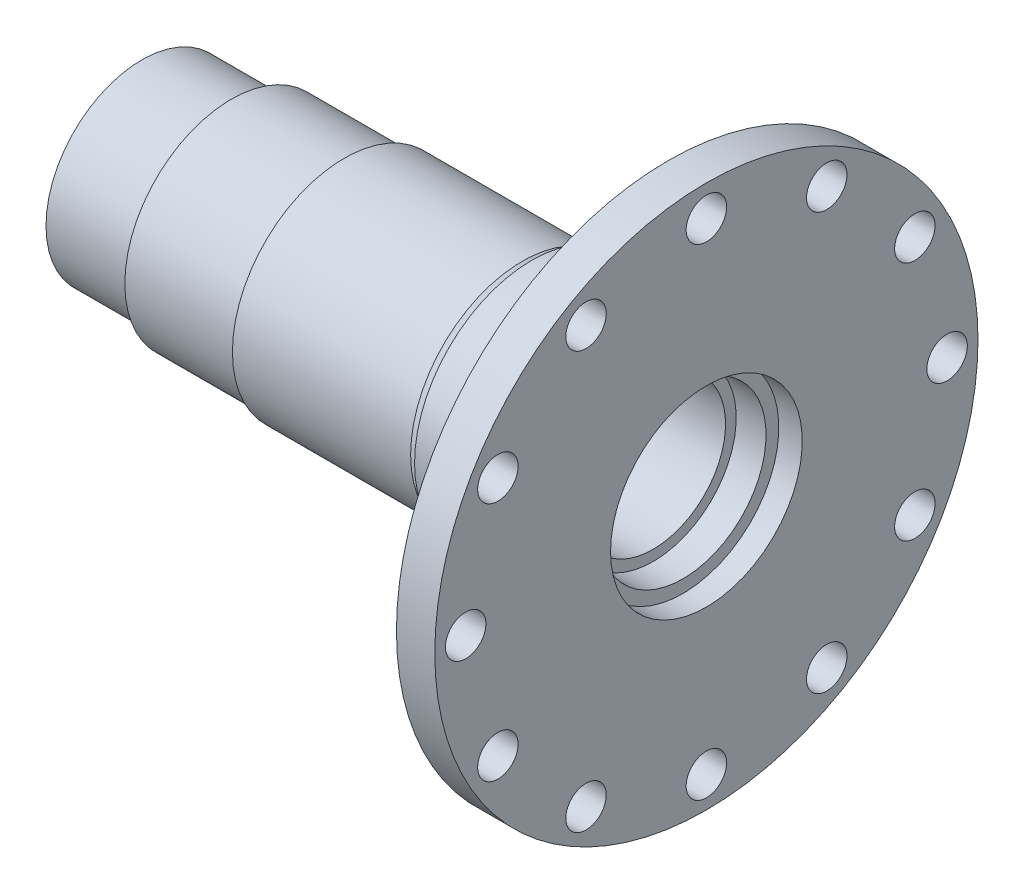
SolidWorks part; units mm, degrees
ref_plane "Спереди" through (0, 0, 0) normal (0, 0, 1) x (1, 0, 0)
ref_plane "Сверху" through (0, 0, 0) normal (0, 1, 0) x (1, 0, 0)
ref_plane "Справа" through (0, 0, 0) normal (1, 0, 0) x (0, 0, -1)
sketch "Эскиз1" plane through (0, 0, 0) normal (0, 0, 1) x (1, 0, 0)
  line L0 (0, 0) -> (265, 0)
  line L1 (0, 0) -> (0, 45)
  line L2 (0, 45) -> (42, 45)
  line L3 (42, 45) -> (42, 50)
  line L4 (42, 50) -> (95, 50)
  line L5 (95, 50) -> (95, 52.5)
  line L6 (95, 52.5) -> (178.6699, 52.5)
  line L7 (178.6699, 52.5) -> (183, 55)
  line L8 (183, 55) -> (215, 55)
  line L9 (215, 55) -> (215, 62.5)
  line L10 (215, 62.5) -> (239, 62.5)
  line L11 (239, 62.5) -> (239, 100)
  line L12 (239, 100) -> (247, 100)
  line L13 (247, 100) -> (247, 127.5)
  line L14 (247, 127.5) -> (265, 127.5)
  line L15 (265, 127.5) -> (265, 0)
revolve "Повернуть1" add sketch "Эскиз1" angle 360 about L0
sketch "Эскиз2" plane through (0, 0, 0) normal (0, 0, 1) x (1, 0, 0)
  line L0 (0, 0) -> (265, 0)
  line L1 (0, 0) -> (0, 31)
  line L2 (0, 31) -> (203.5, 31)
  line L3 (203.5, 31) -> (203.5, 34)
  line L4 (203.5, 34) -> (240, 34)
  line L5 (240, 34) -> (240, 39)
  line L6 (240, 39) -> (254, 39)
  line L7 (254, 39) -> (254, 45)
  line L8 (254, 45) -> (265, 45)
  line L9 (265, 45) -> (265, 0)
revolve "Вырез-Повернуть1" cut sketch "Эскиз2" angle 360 about L0
sketch "Эскиз3" plane through (0, 0, 0) normal (1, 0, 0) x (0, 0, -1)
  circle A0 centre (0, 113) radius 9.5
extrude "Вырез-Вытянуть1" cut sketch "Эскиз3" along normal through all
sketch "Эскиз4" plane through (0, 0, 0) normal (1, 0, 0) x (0, 0, -1)
  circle A0 centre (-56.5, 97.8609) radius 9.5
extrude "Вырез-Вытянуть2" cut sketch "Эскиз4" along normal through all
sketch "Эскиз5" plane through (0, 0, 0) normal (1, 0, 0) x (0, 0, -1)
  circle A0 centre (-97.8609, 56.5) radius 9.5
extrude "Вырез-Вытянуть3" cut sketch "Эскиз5" along normal through all
sketch "Эскиз6" plane through (0, 0, 0) normal (1, 0, 0) x (0, 0, -1)
  circle A0 centre (-113, 0) radius 9.5
extrude "Вырез-Вытянуть4" cut sketch "Эскиз6" along normal through all
sketch "Эскиз7" plane through (0, 0, 0) normal (1, 0, 0) x (0, 0, -1)
  circle A0 centre (-97.8609, -56.5) radius 9.5
extrude "Вырез-Вытянуть5" cut sketch "Эскиз7" along normal through all
sketch "Эскиз8" plane through (0, 0, 0) normal (1, 0, 0) x (0, 0, -1)
  circle A0 centre (-56.5, -97.8609) radius 9.5
extrude "Вырез-Вытянуть6" cut sketch "Эскиз8" along normal through all
sketch "Эскиз9" plane through (0, 0, 0) normal (1, 0, 0) x (0, 0, -1)
  circle A0 centre (0, -113) radius 9.5
extrude "Вырез-Вытянуть7" cut sketch "Эскиз9" along normal through all
sketch "Эскиз10" plane through (0, 0, 0) normal (1, 0, 0) x (0, 0, -1)
  circle A0 centre (56.5, -97.8609) radius 9.5
extrude "Вырез-Вытянуть8" cut sketch "Эскиз10" along normal through all
sketch "Эскиз11" plane through (0, 0, 0) normal (1, 0, 0) x (0, 0, -1)
  circle A0 centre (97.8609, -56.5) radius 9.5
extrude "Вырез-Вытянуть9" cut sketch "Эскиз11" along normal through all
sketch "Эскиз12" plane through (0, 0, 0) normal (1, 0, 0) x (0, 0, -1)
  circle A0 centre (113, 0) radius 9.5
extrude "Вырез-Вытянуть10" cut sketch "Эскиз12" along normal through all
sketch "Эскиз13" plane through (0, 0, 0) normal (1, 0, 0) x (0, 0, -1)
  circle A0 centre (97.8609, 56.5) radius 9.5
extrude "Вырез-Вытянуть11" cut sketch "Эскиз13" along normal through all
sketch "Эскиз14" plane through (0, 0, 0) normal (1, 0, 0) x (0, 0, -1)
  circle A0 centre (56.5, 97.8609) radius 9.5
extrude "Вырез-Вытянуть12" cut sketch "Эскиз14" along normal through all
